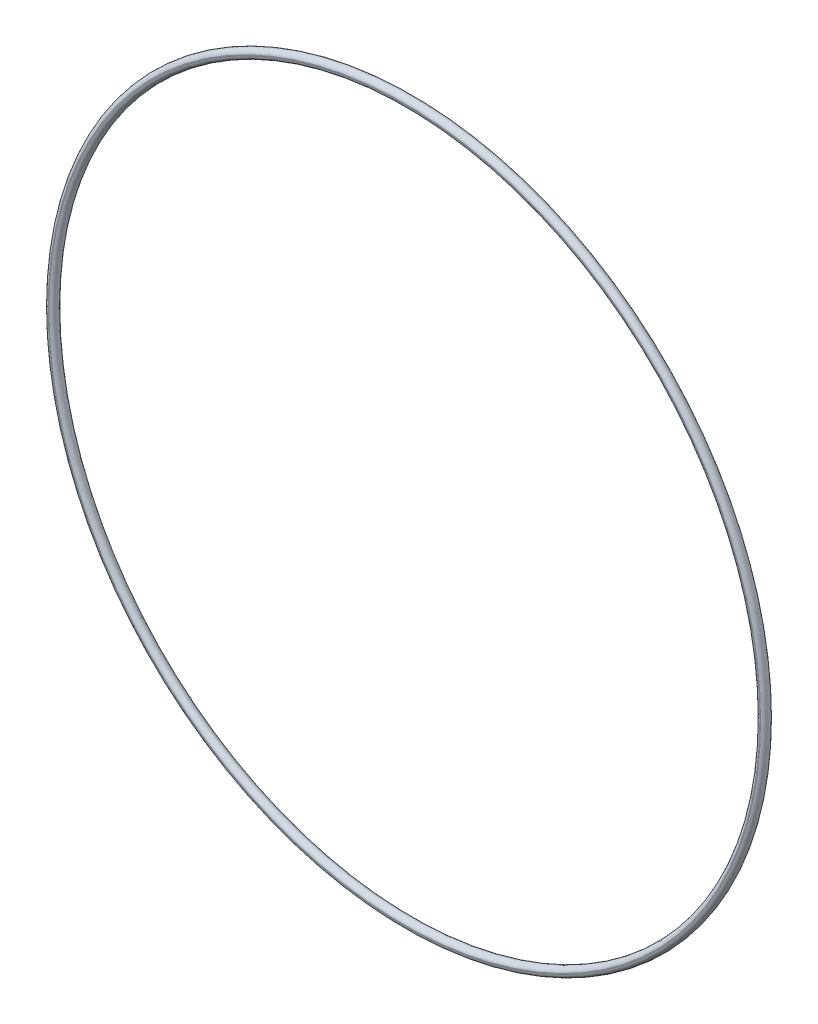
SolidWorks part; units mm, degrees
ref_plane "Front" through (0, 0, 0) normal (0, 0, 1) x (1, 0, 0)
ref_plane "Top" through (0, 0, 0) normal (0, 1, 0) x (1, 0, 0)
ref_plane "Right" through (0, 0, 0) normal (1, 0, 0) x (0, 0, -1)
sketch "Sketch1" plane through (0, 0, 0) normal (1, 0, 0) x (0, -1, 0)
  line L0 (0, -1.3081) -> (0, 1.3081) construction
  line L2 (-55, 0) -> (55, 0) construction
  line L3 (-98.2599, 0) -> (98.2599, 0) construction
  line L4 (99.4608, -1.3037) -> (99.6752, -1.3037)
  line L5 (99.4608, -1.3037) -> (99.4608, 1.3037)
  line L6 (99.4608, 1.3037) -> (99.6752, 1.3037)
  line L7 (99.6752, -1.3037) -> (99.6752, 1.3037)
  line L8 (99.4608, -1.3037) -> (99.6752, 1.3037) construction
  line L9 (99.4608, 1.3037) -> (99.6752, -1.3037) construction
  circle A0 centre (99.568, 0) radius 1.3081
  point P9 (98.2599, 0)
  point P10 (100.8761, 0)
  point P13 (99.568, 1.3081)
  point P14 (99.568, -1.3081)
  dimension "Width" = 2.6162
  dimension "ID" = 196.5198
revolve "Revolve1" add sketch "Sketch1" angle 360 about L0
